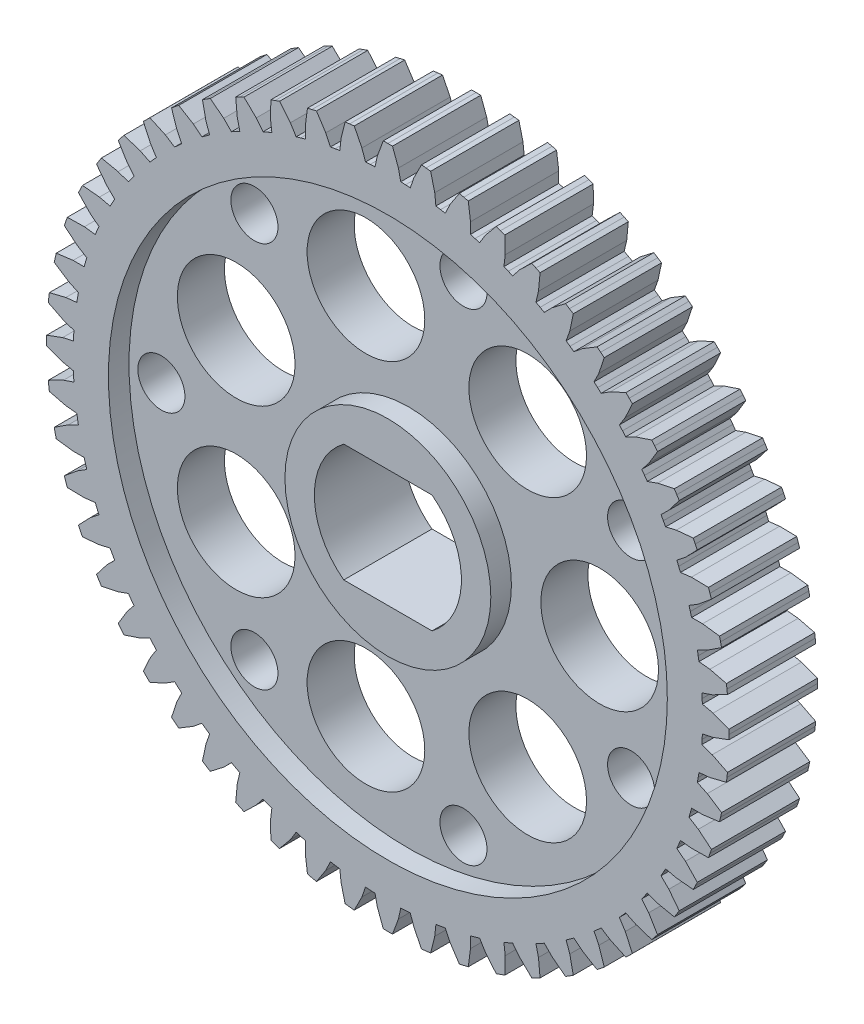
SolidWorks part; units mm, degrees
ref_plane "Front Plane" through (0, 0, 0) normal (0, 0, 1) x (1, 0, 0)
ref_plane "Top Plane" through (0, 0, 0) normal (0, 1, 0) x (1, 0, 0)
ref_plane "Right Plane" through (0, 0, 0) normal (1, 0, 0) x (0, 0, -1)
sketch "Sketch1" plane through (0, 0, 0) normal (0, 0, 1) x (1, 0, 0)
  line L0 (53.4552, -2.1897) -> (55.2775, -1.7881)
  line L1 (55.2775, -1.7881) -> (57.9947, -0.7819)
  line L2 (57.9947, -0.7819) -> (58, 0)
  line L3 (58, 0) -> (57.9947, 0.7819)
  line L4 (57.9947, 0.7819) -> (55.2775, 1.7881)
  line L5 (55.2775, 1.7881) -> (53.4552, 2.1897)
  line L6 (53.4552, 2.1897) -> (53.4158, 2.9998)
  line L7 (53.4158, 2.9998) -> (53.3642, 3.8092)
  line L8 (53.3642, 3.8092) -> (55.1301, 4.4122)
  line L9 (55.1301, 4.4122) -> (57.7176, 5.7163)
  line L10 (57.7176, 5.7163) -> (57.6353, 6.4939)
  line L11 (57.6353, 6.4939) -> (57.5425, 7.2704)
  line L12 (57.5425, 7.2704) -> (54.7297, 7.966)
  line L13 (54.7297, 7.966) -> (52.8739, 8.161)
  line L14 (52.8739, 8.161) -> (52.7441, 8.9616)
  line L15 (52.7441, 8.9616) -> (52.6022, 9.7601)
  line L16 (52.6022, 9.7601) -> (54.2895, 10.5571)
  line L17 (54.2895, 10.5571) -> (56.7147, 12.1427)
  line L18 (56.7147, 12.1427) -> (56.5458, 12.9062)
  line L19 (56.5458, 12.9062) -> (56.3667, 13.6674)
  line L20 (56.3667, 13.6674) -> (53.4937, 14.0437)
  line L21 (53.4937, 14.0437) -> (51.6277, 14.0297)
  line L22 (51.6277, 14.0297) -> (51.4091, 14.8107)
  line L23 (51.4091, 14.8107) -> (51.1787, 15.5883)
  line L24 (51.1787, 15.5883) -> (52.7661, 16.5692)
  line L25 (52.7661, 16.5692) -> (54.9985, 18.4164)
  line L26 (54.9985, 18.4164) -> (54.7452, 19.1562)
  line L27 (54.7452, 19.1562) -> (54.482, 19.8925)
  line L28 (54.482, 19.8925) -> (51.5849, 19.9448)
  line L29 (51.5849, 19.9448) -> (49.7322, 19.7219)
  line L30 (49.7322, 19.7219) -> (49.4276, 20.4736)
  line L31 (49.4276, 20.4736) -> (49.1115, 21.2205)
  line L32 (49.1115, 21.2205) -> (50.5792, 22.373)
  line L33 (50.5792, 22.373) -> (52.5907, 24.4585)
  line L34 (52.5907, 24.4585) -> (52.2562, 25.1653)
  line L35 (52.2562, 25.1653) -> (51.9122, 25.8675)
  line L36 (51.9122, 25.8675) -> (49.0275, 25.5951)
  line L37 (49.0275, 25.5951) -> (47.2114, 25.1662)
  line L38 (47.2114, 25.1662) -> (46.8245, 25.879)
  line L39 (46.8245, 25.879) -> (46.4268, 26.5858)
  line L40 (46.4268, 26.5858) -> (47.7562, 27.8954)
  line L41 (47.7562, 27.8954) -> (49.5216, 30.193)
  line L42 (49.5216, 30.193) -> (49.11, 30.8579)
  line L43 (49.11, 30.8579) -> (48.6895, 31.5171)
  line L44 (48.6895, 31.5171) -> (45.8535, 30.9235)
  line L45 (45.8535, 30.9235) -> (44.0968, 30.2939)
  line L46 (44.0968, 30.2939) -> (43.6325, 30.9589)
  line L47 (43.6325, 30.9589) -> (43.1582, 31.6168)
  line L48 (43.1582, 31.6168) -> (44.3326, 33.0669)
  line L49 (44.3326, 33.0669) -> (45.8296, 35.5478)
  line L50 (45.8296, 35.5478) -> (45.3462, 36.1624)
  line L51 (45.3462, 36.1624) -> (44.8546, 36.7705)
  line L52 (44.8546, 36.7705) -> (42.1028, 35.863)
  line L53 (42.1028, 35.863) -> (40.4277, 35.0407)
  line L54 (40.4277, 35.0407) -> (39.8919, 35.6495)
  line L55 (39.8919, 35.6495) -> (39.3469, 36.2502)
  line L56 (39.3469, 36.2502) -> (40.3515, 37.8227)
  line L57 (40.3515, 37.8227) -> (41.5614, 40.4555)
  line L58 (41.5614, 40.4555) -> (41.0122, 41.0122)
  line L59 (41.0122, 41.0122) -> (40.4555, 41.5614)
  line L60 (40.4555, 41.5614) -> (37.8227, 40.3515)
  line L61 (37.8227, 40.3515) -> (36.2502, 39.3469)
  line L62 (36.2502, 39.3469) -> (35.6495, 39.8919)
  line L63 (35.6495, 39.8919) -> (35.0407, 40.4277)
  line L64 (35.0407, 40.4277) -> (35.863, 42.1028)
  line L65 (35.863, 42.1028) -> (36.7705, 44.8546)
  line L66 (36.7705, 44.8546) -> (36.1624, 45.3462)
  line L67 (36.1624, 45.3462) -> (35.5478, 45.8296)
  line L68 (35.5478, 45.8296) -> (33.0669, 44.3326)
  line L69 (33.0669, 44.3326) -> (31.6168, 43.1582)
  line L70 (31.6168, 43.1582) -> (30.9589, 43.6325)
  line L71 (30.9589, 43.6325) -> (30.2939, 44.0968)
  line L72 (30.2939, 44.0968) -> (30.9235, 45.8535)
  line L73 (30.9235, 45.8535) -> (31.5171, 48.6895)
  line L74 (31.5171, 48.6895) -> (30.8579, 49.11)
  line L75 (30.8579, 49.11) -> (30.193, 49.5216)
  line L76 (30.193, 49.5216) -> (27.8954, 47.7562)
  line L77 (27.8954, 47.7562) -> (26.5858, 46.4268)
  line L78 (26.5858, 46.4268) -> (25.879, 46.8245)
  line L79 (25.879, 46.8245) -> (25.1662, 47.2114)
  line L80 (25.1662, 47.2114) -> (25.5951, 49.0275)
  line L81 (25.5951, 49.0275) -> (25.8675, 51.9122)
  line L82 (25.8675, 51.9122) -> (25.1653, 52.2562)
  line L83 (25.1653, 52.2562) -> (24.4585, 52.5907)
  line L84 (24.4585, 52.5907) -> (22.373, 50.5792)
  line L85 (22.373, 50.5792) -> (21.2205, 49.1115)
  line L86 (21.2205, 49.1115) -> (20.4736, 49.4276)
  line L87 (20.4736, 49.4276) -> (19.7219, 49.7322)
  line L88 (19.7219, 49.7322) -> (19.9448, 51.5849)
  line L89 (19.9448, 51.5849) -> (19.8925, 54.482)
  line L90 (19.8925, 54.482) -> (19.1562, 54.7452)
  line L91 (19.1562, 54.7452) -> (18.4164, 54.9985)
  line L92 (18.4164, 54.9985) -> (16.5692, 52.7661)
  line L93 (16.5692, 52.7661) -> (15.5883, 51.1787)
  line L94 (15.5883, 51.1787) -> (14.8107, 51.4091)
  line L95 (14.8107, 51.4091) -> (14.0297, 51.6277)
  line L96 (14.0297, 51.6277) -> (14.0437, 53.4937)
  line L97 (14.0437, 53.4937) -> (13.6674, 56.3667)
  line L98 (13.6674, 56.3667) -> (12.9062, 56.5458)
  line L99 (12.9062, 56.5458) -> (12.1427, 56.7147)
  line L100 (12.1427, 56.7147) -> (10.5571, 54.2895)
  line L101 (10.5571, 54.2895) -> (9.7601, 52.6022)
  line L102 (9.7601, 52.6022) -> (8.9616, 52.7441)
  line L103 (8.9616, 52.7441) -> (8.161, 52.8739)
  line L104 (8.161, 52.8739) -> (7.966, 54.7297)
  line L105 (7.966, 54.7297) -> (7.2704, 57.5425)
  line L106 (7.2704, 57.5425) -> (6.4939, 57.6353)
  line L107 (6.4939, 57.6353) -> (5.7163, 57.7176)
  line L108 (5.7163, 57.7176) -> (4.4122, 55.1301)
  line L109 (4.4122, 55.1301) -> (3.8092, 53.3642)
  line L110 (3.8092, 53.3642) -> (2.9998, 53.4158)
  line L111 (2.9998, 53.4158) -> (2.1897, 53.4552)
  line L112 (2.1897, 53.4552) -> (1.7881, 55.2775)
  line L113 (1.7881, 55.2775) -> (0.7819, 57.9947)
  line L114 (0.7819, 57.9947) -> (0, 58)
  line L115 (0, 58) -> (-0.7819, 57.9947)
  line L116 (-0.7819, 57.9947) -> (-1.7881, 55.2775)
  line L117 (-1.7881, 55.2775) -> (-2.1897, 53.4552)
  line L118 (-2.1897, 53.4552) -> (-2.9998, 53.4158)
  line L119 (-2.9998, 53.4158) -> (-3.8092, 53.3642)
  line L120 (-3.8092, 53.3642) -> (-4.4122, 55.1301)
  line L121 (-4.4122, 55.1301) -> (-5.7163, 57.7176)
  line L122 (-5.7163, 57.7176) -> (-6.4939, 57.6353)
  line L123 (-6.4939, 57.6353) -> (-7.2704, 57.5425)
  line L124 (-7.2704, 57.5425) -> (-7.966, 54.7297)
  line L125 (-7.966, 54.7297) -> (-8.161, 52.8739)
  line L126 (-8.161, 52.8739) -> (-8.9616, 52.7441)
  line L127 (-8.9616, 52.7441) -> (-9.7601, 52.6022)
  line L128 (-9.7601, 52.6022) -> (-10.5571, 54.2895)
  line L129 (-10.5571, 54.2895) -> (-12.1427, 56.7147)
  line L130 (-12.1427, 56.7147) -> (-12.9062, 56.5458)
  line L131 (-12.9062, 56.5458) -> (-13.6674, 56.3667)
  line L132 (-13.6674, 56.3667) -> (-14.0437, 53.4937)
  line L133 (-14.0437, 53.4937) -> (-14.0297, 51.6277)
  line L134 (-14.0297, 51.6277) -> (-14.8107, 51.4091)
  line L135 (-14.8107, 51.4091) -> (-15.5883, 51.1787)
  line L136 (-15.5883, 51.1787) -> (-16.5692, 52.7661)
  line L137 (-16.5692, 52.7661) -> (-18.4164, 54.9985)
  line L138 (-18.4164, 54.9985) -> (-19.1562, 54.7452)
  line L139 (-19.1562, 54.7452) -> (-19.8925, 54.482)
  line L140 (-19.8925, 54.482) -> (-19.9448, 51.5849)
  line L141 (-19.9448, 51.5849) -> (-19.7219, 49.7322)
  line L142 (-19.7219, 49.7322) -> (-20.4736, 49.4276)
  line L143 (-20.4736, 49.4276) -> (-21.2205, 49.1115)
  line L144 (-21.2205, 49.1115) -> (-22.373, 50.5792)
  line L145 (-22.373, 50.5792) -> (-24.4585, 52.5907)
  line L146 (-24.4585, 52.5907) -> (-25.1653, 52.2562)
  line L147 (-25.1653, 52.2562) -> (-25.8675, 51.9122)
  line L148 (-25.8675, 51.9122) -> (-25.5951, 49.0275)
  line L149 (-25.5951, 49.0275) -> (-25.1662, 47.2114)
  line L150 (-25.1662, 47.2114) -> (-25.879, 46.8245)
  line L151 (-25.879, 46.8245) -> (-26.5858, 46.4268)
  line L152 (-26.5858, 46.4268) -> (-27.8954, 47.7562)
  line L153 (-27.8954, 47.7562) -> (-30.193, 49.5216)
  line L154 (-30.193, 49.5216) -> (-30.8579, 49.11)
  line L155 (-30.8579, 49.11) -> (-31.5171, 48.6895)
  line L156 (-31.5171, 48.6895) -> (-30.9235, 45.8535)
  line L157 (-30.9235, 45.8535) -> (-30.2939, 44.0968)
  line L158 (-30.2939, 44.0968) -> (-30.9589, 43.6325)
  line L159 (-30.9589, 43.6325) -> (-31.6168, 43.1582)
  line L160 (-31.6168, 43.1582) -> (-33.0669, 44.3326)
  line L161 (-33.0669, 44.3326) -> (-35.5478, 45.8296)
  line L162 (-35.5478, 45.8296) -> (-36.1624, 45.3462)
  line L163 (-36.1624, 45.3462) -> (-36.7705, 44.8546)
  line L164 (-36.7705, 44.8546) -> (-35.863, 42.1028)
  line L165 (-35.863, 42.1028) -> (-35.0407, 40.4277)
  line L166 (-35.0407, 40.4277) -> (-35.6495, 39.8919)
  line L167 (-35.6495, 39.8919) -> (-36.2502, 39.3469)
  line L168 (-36.2502, 39.3469) -> (-37.8227, 40.3515)
  line L169 (-37.8227, 40.3515) -> (-40.4555, 41.5614)
  line L170 (-40.4555, 41.5614) -> (-41.0122, 41.0122)
  line L171 (-41.0122, 41.0122) -> (-41.5614, 40.4555)
  line L172 (-41.5614, 40.4555) -> (-40.3515, 37.8227)
  line L173 (-40.3515, 37.8227) -> (-39.3469, 36.2502)
  line L174 (-39.3469, 36.2502) -> (-39.8919, 35.6495)
  line L175 (-39.8919, 35.6495) -> (-40.4277, 35.0407)
  line L176 (-40.4277, 35.0407) -> (-42.1028, 35.863)
  line L177 (-42.1028, 35.863) -> (-44.8546, 36.7705)
  line L178 (-44.8546, 36.7705) -> (-45.3462, 36.1624)
  line L179 (-45.3462, 36.1624) -> (-45.8296, 35.5478)
  line L180 (-45.8296, 35.5478) -> (-44.3326, 33.0669)
  line L181 (-44.3326, 33.0669) -> (-43.1582, 31.6168)
  line L182 (-43.1582, 31.6168) -> (-43.6325, 30.9589)
  line L183 (-43.6325, 30.9589) -> (-44.0968, 30.2939)
  line L184 (-44.0968, 30.2939) -> (-45.8535, 30.9235)
  line L185 (-45.8535, 30.9235) -> (-48.6895, 31.5171)
  line L186 (-48.6895, 31.5171) -> (-49.11, 30.8579)
  line L187 (-49.11, 30.8579) -> (-49.5216, 30.193)
  line L188 (-49.5216, 30.193) -> (-47.7562, 27.8954)
  line L189 (-47.7562, 27.8954) -> (-46.4268, 26.5858)
  line L190 (-46.4268, 26.5858) -> (-46.8245, 25.879)
  line L191 (-46.8245, 25.879) -> (-47.2114, 25.1662)
  line L192 (-47.2114, 25.1662) -> (-49.0275, 25.5951)
  line L193 (-49.0275, 25.5951) -> (-51.9122, 25.8675)
  line L194 (-51.9122, 25.8675) -> (-52.2562, 25.1653)
  line L195 (-52.2562, 25.1653) -> (-52.5907, 24.4585)
  line L196 (-52.5907, 24.4585) -> (-50.5792, 22.373)
  line L197 (-50.5792, 22.373) -> (-49.1115, 21.2205)
  line L198 (-49.1115, 21.2205) -> (-49.4276, 20.4736)
  line L199 (-49.4276, 20.4736) -> (-49.7322, 19.7219)
  line L200 (-49.7322, 19.7219) -> (-51.5849, 19.9448)
  line L201 (-51.5849, 19.9448) -> (-54.482, 19.8925)
  line L202 (-54.482, 19.8925) -> (-54.7452, 19.1562)
  line L203 (-54.7452, 19.1562) -> (-54.9985, 18.4164)
  line L204 (-54.9985, 18.4164) -> (-52.7661, 16.5692)
  line L205 (-52.7661, 16.5692) -> (-51.1787, 15.5883)
  line L206 (-51.1787, 15.5883) -> (-51.4091, 14.8107)
  line L207 (-51.4091, 14.8107) -> (-51.6277, 14.0297)
  line L208 (-51.6277, 14.0297) -> (-53.4937, 14.0437)
  line L209 (-53.4937, 14.0437) -> (-56.3667, 13.6674)
  line L210 (-56.3667, 13.6674) -> (-56.5458, 12.9062)
  line L211 (-56.5458, 12.9062) -> (-56.7147, 12.1427)
  line L212 (-56.7147, 12.1427) -> (-54.2895, 10.5571)
  line L213 (-54.2895, 10.5571) -> (-52.6022, 9.7601)
  line L214 (-52.6022, 9.7601) -> (-52.7441, 8.9616)
  line L215 (-52.7441, 8.9616) -> (-52.8739, 8.161)
  line L216 (-52.8739, 8.161) -> (-54.7297, 7.966)
  line L217 (-54.7297, 7.966) -> (-57.5425, 7.2704)
  line L218 (-57.5425, 7.2704) -> (-57.6353, 6.4939)
  line L219 (-57.6353, 6.4939) -> (-57.7176, 5.7163)
  line L220 (-57.7176, 5.7163) -> (-55.1301, 4.4122)
  line L221 (-55.1301, 4.4122) -> (-53.3642, 3.8092)
  line L222 (-53.3642, 3.8092) -> (-53.4158, 2.9998)
  line L223 (-53.4158, 2.9998) -> (-53.4552, 2.1897)
  line L224 (-53.4552, 2.1897) -> (-55.2775, 1.7881)
  line L225 (-55.2775, 1.7881) -> (-57.9947, 0.7819)
  line L226 (-57.9947, 0.7819) -> (-58, 0)
  line L227 (-58, 0) -> (-57.9947, -0.7819)
  line L228 (-57.9947, -0.7819) -> (-55.2775, -1.7881)
  line L229 (-55.2775, -1.7881) -> (-53.4552, -2.1897)
  line L230 (-53.4552, -2.1897) -> (-53.4158, -2.9998)
  line L231 (-53.4158, -2.9998) -> (-53.3642, -3.8092)
  line L232 (-53.3642, -3.8092) -> (-55.1301, -4.4122)
  line L233 (-55.1301, -4.4122) -> (-57.7176, -5.7163)
  line L234 (-57.7176, -5.7163) -> (-57.6353, -6.4939)
  line L235 (-57.6353, -6.4939) -> (-57.5425, -7.2704)
  line L236 (-57.5425, -7.2704) -> (-54.7297, -7.966)
  line L237 (-54.7297, -7.966) -> (-52.8739, -8.161)
  line L238 (-52.8739, -8.161) -> (-52.7441, -8.9616)
  line L239 (-52.7441, -8.9616) -> (-52.6022, -9.7601)
  line L240 (-52.6022, -9.7601) -> (-54.2895, -10.5571)
  line L241 (-54.2895, -10.5571) -> (-56.7147, -12.1427)
  line L242 (-56.7147, -12.1427) -> (-56.5458, -12.9062)
  line L243 (-56.5458, -12.9062) -> (-56.3667, -13.6674)
  line L244 (-56.3667, -13.6674) -> (-53.4937, -14.0437)
  line L245 (-53.4937, -14.0437) -> (-51.6277, -14.0297)
  line L246 (-51.6277, -14.0297) -> (-51.4091, -14.8107)
  line L247 (-51.4091, -14.8107) -> (-51.1787, -15.5883)
  line L248 (-51.1787, -15.5883) -> (-52.7661, -16.5692)
  line L249 (-52.7661, -16.5692) -> (-54.9985, -18.4164)
  line L250 (-54.9985, -18.4164) -> (-54.7452, -19.1562)
  line L251 (-54.7452, -19.1562) -> (-54.482, -19.8925)
  line L252 (-54.482, -19.8925) -> (-51.5849, -19.9448)
  line L253 (-51.5849, -19.9448) -> (-49.7322, -19.7219)
  line L254 (-49.7322, -19.7219) -> (-49.4276, -20.4736)
  line L255 (-49.4276, -20.4736) -> (-49.1115, -21.2205)
  line L256 (-49.1115, -21.2205) -> (-50.5792, -22.373)
  line L257 (-50.5792, -22.373) -> (-52.5907, -24.4585)
  line L258 (-52.5907, -24.4585) -> (-52.2562, -25.1653)
  line L259 (-52.2562, -25.1653) -> (-51.9122, -25.8675)
  line L260 (-51.9122, -25.8675) -> (-49.0275, -25.5951)
  line L261 (-49.0275, -25.5951) -> (-47.2114, -25.1662)
  line L262 (-47.2114, -25.1662) -> (-46.8245, -25.879)
  line L263 (-46.8245, -25.879) -> (-46.4268, -26.5858)
  line L264 (-46.4268, -26.5858) -> (-47.7562, -27.8954)
  line L265 (-47.7562, -27.8954) -> (-49.5216, -30.193)
  line L266 (-49.5216, -30.193) -> (-49.11, -30.8579)
  line L267 (-49.11, -30.8579) -> (-48.6895, -31.5171)
  line L268 (-48.6895, -31.5171) -> (-45.8535, -30.9235)
  line L269 (-45.8535, -30.9235) -> (-44.0968, -30.2939)
  line L270 (-44.0968, -30.2939) -> (-43.6325, -30.9589)
  line L271 (-43.6325, -30.9589) -> (-43.1582, -31.6168)
  line L272 (-43.1582, -31.6168) -> (-44.3326, -33.0669)
  line L273 (-44.3326, -33.0669) -> (-45.8296, -35.5478)
  line L274 (-45.8296, -35.5478) -> (-45.3462, -36.1624)
  line L275 (-45.3462, -36.1624) -> (-44.8546, -36.7705)
  line L276 (-44.8546, -36.7705) -> (-42.1028, -35.863)
  line L277 (-42.1028, -35.863) -> (-40.4277, -35.0407)
  line L278 (-40.4277, -35.0407) -> (-39.8919, -35.6495)
  line L279 (-39.8919, -35.6495) -> (-39.3469, -36.2502)
  line L280 (-39.3469, -36.2502) -> (-40.3515, -37.8227)
  line L281 (-40.3515, -37.8227) -> (-41.5614, -40.4555)
  line L282 (-41.5614, -40.4555) -> (-41.0122, -41.0122)
  line L283 (-41.0122, -41.0122) -> (-40.4555, -41.5614)
  line L284 (-40.4555, -41.5614) -> (-37.8227, -40.3515)
  line L285 (-37.8227, -40.3515) -> (-36.2502, -39.3469)
  line L286 (-36.2502, -39.3469) -> (-35.6495, -39.8919)
  line L287 (-35.6495, -39.8919) -> (-35.0407, -40.4277)
  line L288 (-35.0407, -40.4277) -> (-35.863, -42.1028)
  line L289 (-35.863, -42.1028) -> (-36.7705, -44.8546)
  line L290 (-36.7705, -44.8546) -> (-36.1624, -45.3462)
  line L291 (-36.1624, -45.3462) -> (-35.5478, -45.8296)
  line L292 (-35.5478, -45.8296) -> (-33.0669, -44.3326)
  line L293 (-33.0669, -44.3326) -> (-31.6168, -43.1582)
  line L294 (-31.6168, -43.1582) -> (-30.9589, -43.6325)
  line L295 (-30.9589, -43.6325) -> (-30.2939, -44.0968)
  line L296 (-30.2939, -44.0968) -> (-30.9235, -45.8535)
  line L297 (-30.9235, -45.8535) -> (-31.5171, -48.6895)
  line L298 (-31.5171, -48.6895) -> (-30.8579, -49.11)
  line L299 (-30.8579, -49.11) -> (-30.193, -49.5216)
  line L300 (-30.193, -49.5216) -> (-27.8954, -47.7562)
  line L301 (-27.8954, -47.7562) -> (-26.5858, -46.4268)
  line L302 (-26.5858, -46.4268) -> (-25.879, -46.8245)
  line L303 (-25.879, -46.8245) -> (-25.1662, -47.2114)
  line L304 (-25.1662, -47.2114) -> (-25.5951, -49.0275)
  line L305 (-25.5951, -49.0275) -> (-25.8675, -51.9122)
  line L306 (-25.8675, -51.9122) -> (-25.1653, -52.2562)
  line L307 (-25.1653, -52.2562) -> (-24.4585, -52.5907)
  line L308 (-24.4585, -52.5907) -> (-22.373, -50.5792)
  line L309 (-22.373, -50.5792) -> (-21.2205, -49.1115)
  line L310 (-21.2205, -49.1115) -> (-20.4736, -49.4276)
  line L311 (-20.4736, -49.4276) -> (-19.7219, -49.7322)
  line L312 (-19.7219, -49.7322) -> (-19.9448, -51.5849)
  line L313 (-19.9448, -51.5849) -> (-19.8925, -54.482)
  line L314 (-19.8925, -54.482) -> (-19.1562, -54.7452)
  line L315 (-19.1562, -54.7452) -> (-18.4164, -54.9985)
  line L316 (-18.4164, -54.9985) -> (-16.5692, -52.7661)
  line L317 (-16.5692, -52.7661) -> (-15.5883, -51.1787)
  line L318 (-15.5883, -51.1787) -> (-14.8107, -51.4091)
  line L319 (-14.8107, -51.4091) -> (-14.0297, -51.6277)
  line L320 (-14.0297, -51.6277) -> (-14.0437, -53.4937)
  line L321 (-14.0437, -53.4937) -> (-13.6674, -56.3667)
  line L322 (-13.6674, -56.3667) -> (-12.9062, -56.5458)
  line L323 (-12.9062, -56.5458) -> (-12.1427, -56.7147)
  line L324 (-12.1427, -56.7147) -> (-10.5571, -54.2895)
  line L325 (-10.5571, -54.2895) -> (-9.7601, -52.6022)
  line L326 (-9.7601, -52.6022) -> (-8.9616, -52.7441)
  line L327 (-8.9616, -52.7441) -> (-8.161, -52.8739)
  line L328 (-8.161, -52.8739) -> (-7.966, -54.7297)
  line L329 (-7.966, -54.7297) -> (-7.2704, -57.5425)
  line L330 (-7.2704, -57.5425) -> (-6.4939, -57.6353)
  line L331 (-6.4939, -57.6353) -> (-5.7163, -57.7176)
  line L332 (-5.7163, -57.7176) -> (-4.4122, -55.1301)
  line L333 (-4.4122, -55.1301) -> (-3.8092, -53.3642)
  line L334 (-3.8092, -53.3642) -> (-2.9998, -53.4158)
  line L335 (-2.9998, -53.4158) -> (-2.1897, -53.4552)
  line L336 (-2.1897, -53.4552) -> (-1.7881, -55.2775)
  line L337 (-1.7881, -55.2775) -> (-0.7819, -57.9947)
  line L338 (-0.7819, -57.9947) -> (0, -58)
  line L339 (0, -58) -> (0.7819, -57.9947)
  line L340 (0.7819, -57.9947) -> (1.7881, -55.2775)
  line L341 (1.7881, -55.2775) -> (2.1897, -53.4552)
  line L342 (2.1897, -53.4552) -> (2.9998, -53.4158)
  line L343 (2.9998, -53.4158) -> (3.8092, -53.3642)
  line L344 (3.8092, -53.3642) -> (4.4122, -55.1301)
  line L345 (4.4122, -55.1301) -> (5.7163, -57.7176)
  line L346 (5.7163, -57.7176) -> (6.4939, -57.6353)
  line L347 (6.4939, -57.6353) -> (7.2704, -57.5425)
  line L348 (7.2704, -57.5425) -> (7.966, -54.7297)
  line L349 (7.966, -54.7297) -> (8.161, -52.8739)
  line L350 (8.161, -52.8739) -> (8.9616, -52.7441)
  line L351 (8.9616, -52.7441) -> (9.7601, -52.6022)
  line L352 (9.7601, -52.6022) -> (10.5571, -54.2895)
  line L353 (10.5571, -54.2895) -> (12.1427, -56.7147)
  line L354 (12.1427, -56.7147) -> (12.9062, -56.5458)
  line L355 (12.9062, -56.5458) -> (13.6674, -56.3667)
  line L356 (13.6674, -56.3667) -> (14.0437, -53.4937)
  line L357 (14.0437, -53.4937) -> (14.0297, -51.6277)
  line L358 (14.0297, -51.6277) -> (14.8107, -51.4091)
  line L359 (14.8107, -51.4091) -> (15.5883, -51.1787)
  line L360 (15.5883, -51.1787) -> (16.5692, -52.7661)
  line L361 (16.5692, -52.7661) -> (18.4164, -54.9985)
  line L362 (18.4164, -54.9985) -> (19.1562, -54.7452)
  line L363 (19.1562, -54.7452) -> (19.8925, -54.482)
  line L364 (19.8925, -54.482) -> (19.9448, -51.5849)
  line L365 (19.9448, -51.5849) -> (19.7219, -49.7322)
  line L366 (19.7219, -49.7322) -> (20.4736, -49.4276)
  line L367 (20.4736, -49.4276) -> (21.2205, -49.1115)
  line L368 (21.2205, -49.1115) -> (22.373, -50.5792)
  line L369 (22.373, -50.5792) -> (24.4585, -52.5907)
  line L370 (24.4585, -52.5907) -> (25.1653, -52.2562)
  line L371 (25.1653, -52.2562) -> (25.8675, -51.9122)
  line L372 (25.8675, -51.9122) -> (25.5951, -49.0275)
  line L373 (25.5951, -49.0275) -> (25.1662, -47.2114)
  line L374 (25.1662, -47.2114) -> (25.879, -46.8245)
  line L375 (25.879, -46.8245) -> (26.5858, -46.4268)
  line L376 (26.5858, -46.4268) -> (27.8954, -47.7562)
  line L377 (27.8954, -47.7562) -> (30.193, -49.5216)
  line L378 (30.193, -49.5216) -> (30.8579, -49.11)
  line L379 (30.8579, -49.11) -> (31.5171, -48.6895)
  line L380 (31.5171, -48.6895) -> (30.9235, -45.8535)
  line L381 (30.9235, -45.8535) -> (30.2939, -44.0968)
  line L382 (30.2939, -44.0968) -> (30.9589, -43.6325)
  line L383 (30.9589, -43.6325) -> (31.6168, -43.1582)
  line L384 (31.6168, -43.1582) -> (33.0669, -44.3326)
  line L385 (33.0669, -44.3326) -> (35.5478, -45.8296)
  line L386 (35.5478, -45.8296) -> (36.1624, -45.3462)
  line L387 (36.1624, -45.3462) -> (36.7705, -44.8546)
  line L388 (36.7705, -44.8546) -> (35.863, -42.1028)
  line L389 (35.863, -42.1028) -> (35.0407, -40.4277)
  line L390 (35.0407, -40.4277) -> (35.6495, -39.8919)
  line L391 (35.6495, -39.8919) -> (36.2502, -39.3469)
  line L392 (36.2502, -39.3469) -> (37.8227, -40.3515)
  line L393 (37.8227, -40.3515) -> (40.4555, -41.5614)
  line L394 (40.4555, -41.5614) -> (41.0122, -41.0122)
  line L395 (41.0122, -41.0122) -> (41.5614, -40.4555)
  line L396 (41.5614, -40.4555) -> (40.3515, -37.8227)
  line L397 (40.3515, -37.8227) -> (39.3469, -36.2502)
  line L398 (39.3469, -36.2502) -> (39.8919, -35.6495)
  line L399 (39.8919, -35.6495) -> (40.4277, -35.0407)
  line L400 (40.4277, -35.0407) -> (42.1028, -35.863)
  line L401 (42.1028, -35.863) -> (44.8546, -36.7705)
  line L402 (44.8546, -36.7705) -> (45.3462, -36.1624)
  line L403 (45.3462, -36.1624) -> (45.8296, -35.5478)
  line L404 (45.8296, -35.5478) -> (44.3326, -33.0669)
  line L405 (44.3326, -33.0669) -> (43.1582, -31.6168)
  line L406 (43.1582, -31.6168) -> (43.6325, -30.9589)
  line L407 (43.6325, -30.9589) -> (44.0968, -30.2939)
  line L408 (44.0968, -30.2939) -> (45.8535, -30.9235)
  line L409 (45.8535, -30.9235) -> (48.6895, -31.5171)
  line L410 (48.6895, -31.5171) -> (49.11, -30.8579)
  line L411 (49.11, -30.8579) -> (49.5216, -30.193)
  line L412 (49.5216, -30.193) -> (47.7562, -27.8954)
  line L413 (47.7562, -27.8954) -> (46.4268, -26.5858)
  line L414 (46.4268, -26.5858) -> (46.8245, -25.879)
  line L415 (46.8245, -25.879) -> (47.2114, -25.1662)
  line L416 (47.2114, -25.1662) -> (49.0275, -25.5951)
  line L417 (49.0275, -25.5951) -> (51.9122, -25.8675)
  line L418 (51.9122, -25.8675) -> (52.2562, -25.1653)
  line L419 (52.2562, -25.1653) -> (52.5907, -24.4585)
  line L420 (52.5907, -24.4585) -> (50.5792, -22.373)
  line L421 (50.5792, -22.373) -> (49.1115, -21.2205)
  line L422 (49.1115, -21.2205) -> (49.4276, -20.4736)
  line L423 (49.4276, -20.4736) -> (49.7322, -19.7219)
  line L424 (49.7322, -19.7219) -> (51.5849, -19.9448)
  line L425 (51.5849, -19.9448) -> (54.482, -19.8925)
  line L426 (54.482, -19.8925) -> (54.7452, -19.1562)
  line L427 (54.7452, -19.1562) -> (54.9985, -18.4164)
  line L428 (54.9985, -18.4164) -> (52.7661, -16.5692)
  line L429 (52.7661, -16.5692) -> (51.1787, -15.5883)
  line L430 (51.1787, -15.5883) -> (51.4091, -14.8107)
  line L431 (51.4091, -14.8107) -> (51.6277, -14.0297)
  line L432 (51.6277, -14.0297) -> (53.4937, -14.0437)
  line L433 (53.4937, -14.0437) -> (56.3667, -13.6674)
  line L434 (56.3667, -13.6674) -> (56.5458, -12.9062)
  line L435 (56.5458, -12.9062) -> (56.7147, -12.1427)
  line L436 (56.7147, -12.1427) -> (54.2895, -10.5571)
  line L437 (54.2895, -10.5571) -> (52.6022, -9.7601)
  line L438 (52.6022, -9.7601) -> (52.7441, -8.9616)
  line L439 (52.7441, -8.9616) -> (52.8739, -8.161)
  line L440 (52.8739, -8.161) -> (54.7297, -7.966)
  line L441 (54.7297, -7.966) -> (57.5425, -7.2704)
  line L442 (57.5425, -7.2704) -> (57.6353, -6.4939)
  line L443 (57.6353, -6.4939) -> (57.7176, -5.7163)
  line L444 (57.7176, -5.7163) -> (55.1301, -4.4122)
  line L445 (55.1301, -4.4122) -> (53.3642, -3.8092)
  line L446 (53.3642, -3.8092) -> (53.4158, -2.9998)
  line L447 (53.4158, -2.9998) -> (53.4552, -2.1897)
extrude "Gear_B_56T_Involute" add sketch "Sketch1" along normal blind 15
sketch "Sketch2" plane through (0, 0, 0) normal (0, 0, 1) x (1, 0, 0)
  circle A0 centre (0, 0) radius 47.5
extrude "Web_Recess_Back_D95" cut sketch "Sketch2" along normal blind 3.5
ref_plane "Plane_FrontFace_15mm" through (0, 0, 15) normal (0, 0, 1) x (1, 0, 0)
sketch "Sketch3" plane through (0, 0, 15) normal (0, 0, 1) x (1, 0, 0)
  circle A0 centre (0, 0) radius 47.5
extrude "Web_Recess_Front_D95" cut sketch "Sketch3" against normal blind 3.5
sketch "Sketch4" plane through (0, 0, 0) normal (0, 0, 1) x (1, 0, 0)
  circle A0 centre (0, 0) radius 17.5
extrude "Center_Hub_D35" add sketch "Sketch4" along normal blind 15
sketch "Sketch5" plane through (0, 0, 0) normal (0, 0, 1) x (1, 0, 0)
  line L0 (-7.5, 10) -> (7.5, 10)
  line L1 (7.5, -10) -> (-7.5, -10)
  arc A0 (7.5, 10) -> (7.5, -10) centre (0, 0) cw
  arc A1 (-7.5, -10) -> (-7.5, 10) centre (0, 0) cw
extrude "Double_Flat_Bore_D25_20mm" cut sketch "Sketch5" against normal through all and the other way through all
sketch "Sketch6" plane through (0, 0, 0) normal (0, 0, 1) x (1, 0, 0)
  circle A0 centre (32.5, 0) radius 10
  circle A1 centre (20.2634, 25.4095) radius 10
  circle A2 centre (-7.2319, 31.6852) radius 10
  circle A3 centre (-29.2815, 14.1012) radius 10
  circle A4 centre (-29.2815, -14.1012) radius 10
  circle A5 centre (-7.2319, -31.6852) radius 10
  circle A6 centre (20.2634, -25.4095) radius 10
extrude "Holes_7x_D20_PCD65" cut sketch "Sketch6" against normal through all and the other way through all
sketch "Sketch7" plane through (0, 0, 0) normal (0, 0, 1) x (1, 0, 0)
  circle A0 centre (37.8407, 18.2231) radius 4
  circle A1 centre (9.3459, 40.947) radius 4
  circle A2 centre (-26.1866, 32.8369) radius 4
  circle A3 centre (-42, 0) radius 4
  circle A4 centre (-26.1866, -32.8369) radius 4
  circle A5 centre (9.3459, -40.947) radius 4
  circle A6 centre (37.8407, -18.2231) radius 4
extrude "Holes_7x_D8_PCD84" cut sketch "Sketch7" against normal through all and the other way through all
